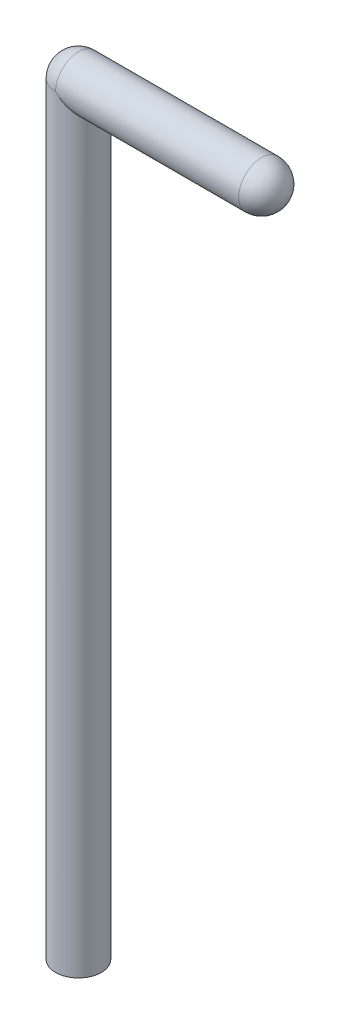
SolidWorks part; units mm, degrees
ref_plane "前视基准面" through (0, 0, 0) normal (0, 0, 1) x (1, 0, 0)
ref_plane "上视基准面" through (0, 0, 0) normal (0, 1, 0) x (1, 0, 0)
ref_plane "右视基准面" through (0, 0, 0) normal (1, 0, 0) x (0, 0, -1)
other "Configuration Table"
sketch "草图1" plane through (0, 0, 0) normal (0, 1, 0) x (1, 0, 0)
  circle A0 centre (0, 0) radius 0.75
  dimension "D1" = 1.5
extrude "凸台-拉伸1" add sketch "草图1" along normal blind 25
sketch "草图2" plane through (0, 0, 0) normal (0, 0, 1) x (1, 0, 0)
  line L2 (0.75, 25) -> (-0.75, 25) construction
  line L3 (0, 25.75) -> (0, 24.25)
  arc A1 (0, 24.25) -> (0, 25.75) centre (0, 25) ccw
revolve "旋转1" add sketch "草图2" angle 360 about L3
sketch "草图3" plane through (0, 0, 0) normal (1, 0, 0) x (0, 0, -1)
  line L0 (-0.75, 25) -> (0.75, 25) construction
  circle A0 centre (0, 25) radius 0.75
  dimension "D1" = 1.5
extrude "凸台-拉伸2" add sketch "草图3" along normal blind 6
sketch "草图4" plane through (6, 0, 0) normal (1, 0, 0) x (0, 0, -1)
  line L0 (0, 25.75) -> (0, 24.25)
  arc A0 (0, 24.25) -> (0, 25.75) centre (0, 25) ccw
  circle A1 centre (0, 25) radius 0.75 construction
  dimension "D1" = 0.75
revolve "旋转2" add sketch "草图4" angle 360 about L0
ref_plane "基准面1" through (0, 25, 0) normal (0, 1, 0) x (1, 0, 0)
sketch "草图5" plane through (0, 25, 0) normal (0, 1, 0) x (1, 0, 0)
  line L0 (6, 0.75) -> (6, -0.75) construction
  circle A0 centre (6, 0) radius 1
  dimension "D1" = 2
